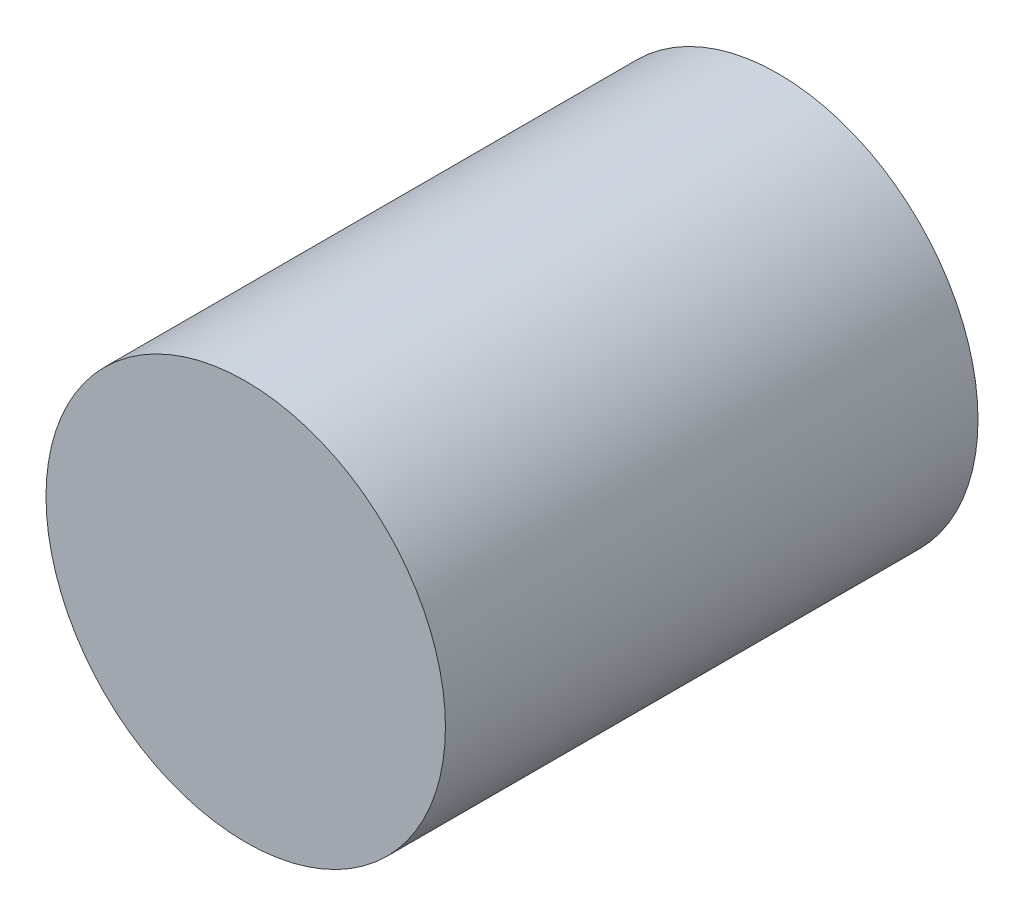
SolidWorks part; units mm, degrees
ref_plane "Front Plane" through (0, 0, 0) normal (0, 0, 1) x (1, 0, 0)
ref_plane "Top Plane" through (0, 0, 0) normal (0, 1, 0) x (1, 0, 0)
ref_plane "Right Plane" through (0, 0, 0) normal (1, 0, 0) x (0, 0, -1)
sketch "Sketch2" plane through (0, 0, 0) normal (0, 0, 1) x (1, 0, 0)
  circle A0 centre (0, 0) radius 7.5
  dimension "D1" = 15
extrude "Boss-Extrude2" add sketch "Sketch2" along normal blind 20
